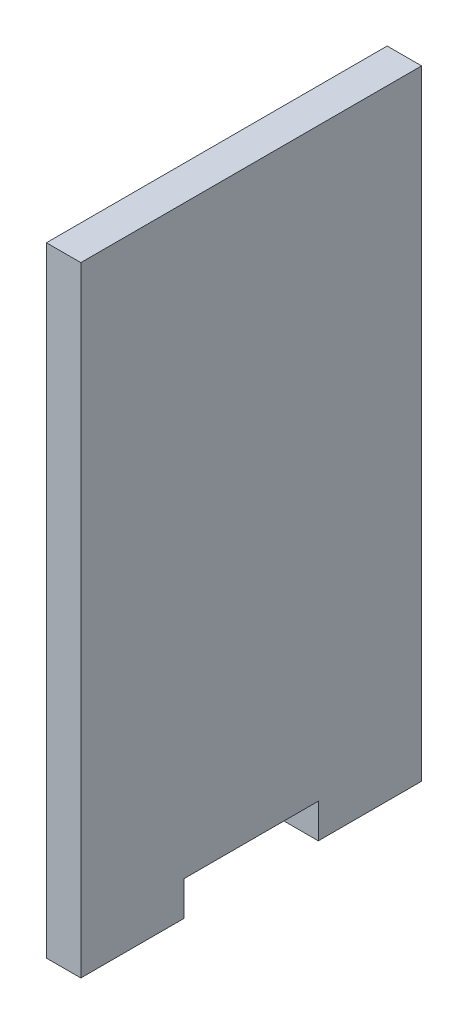
SolidWorks part; units mm, degrees
ref_plane "정면" through (0, 0, 0) normal (0, 0, 1) x (1, 0, 0)
ref_plane "윗면" through (0, 0, 0) normal (0, 1, 0) x (1, 0, 0)
ref_plane "우측면" through (0, 0, 0) normal (1, 0, 0) x (0, 0, -1)
sketch "스케치1" plane through (0, 0, 0) normal (1, 0, 0) x (0, 0, -1)
  line L1 (0, 43.267) -> (49.5, 43.267)
  line L2 (0, 43.267) -> (0, -41.733)
  line L3 (0, -41.733) -> (49.5, -41.733)
  line L4 (49.5, 43.267) -> (49.5, -41.733)
  dimension "D1" = 49.5
  dimension "D2" = 85
extrude "보스-돌출1" add sketch "스케치1" along normal blind 5
sketch "스케치2" plane through (5, 0, 0) normal (1, 0, 0) x (0, 0, -1)
  line L0 (0, -41.733) -> (49.5, -41.733) construction
  line L1 (0, -41.733) -> (91, -41.733)
  line L2 (0, -41.733) -> (0, -191.733)
  line L3 (0, -191.733) -> (91, -191.733)
  line L4 (91, -41.733) -> (91, -191.733)
  line L6 (0, 43.267) -> (0, -41.733) construction
  line L7 (91, -41.733) -> (90.889, 3.2199) construction
  dimension "D1" = 91
  dimension "D2" = 150
extrude "보스-돌출2" [suppressed] add sketch "스케치2" against normal blind 5
fillet "필렛1" [suppressed] radius 5
hole_wizard "M3 소켓 머리 캡 나사용 카운터보어1" [suppressed] positions "스케치4" profile "스케치3" counterbore size "M3" standard "KS"
sketch "스케치4" plane through (5, 0, 0) normal (1, 0, 0) x (0, 0, -1)
  line L0 (91, 23.267) -> (70.5, 23.267) construction
  line L2 (70.5, 23.267) -> (20.5, 23.267) construction
  line L3 (20.5, 23.267) -> (0, 23.267) construction
  line L5 (91, 43.267) -> (0, 43.267) construction
  point P2 (70.5, 23.267)
  point P6 (20.5, 23.267)
  dimension "D1" = 50
  dimension "D2" = 20
sketch "스케치3" plane through (5, 23.267, -70.5) normal (0, 1, 0) x (0, 0, -1)
  line L0 (0, 0) -> (0, 5)
  line L1 (0, 5) -> (1.7, 5)
  line L3 (1.7, 5) -> (1.7, 3)
  line L4 (1.7, 3) -> (3.25, 3)
  line L5 (3.25, 3) -> (3.25, 0)
  line L7 (3.25, 0) -> (0, 0)
  line L11 (0, -6.35) -> (0, 107.95) construction
  dimension "관통 구멍 지름" = 3.4
  dimension "관통 구멍 깊이" = 5
  dimension "카운터보어 지름" = 6.5
  dimension "카운터보어 깊이" = 3
hole_wizard "M3 소켓 머리 캡 나사용 카운터보어2" [suppressed] positions "스케치9" profile "스케치8" counterbore size "M3" standard "KS"
sketch "스케치9" plane through (0, 0, 0) normal (-1, 0, 0) x (0, 0, 1)
  line L0 (0, -39.233) -> (-12.25, -39.233) construction
  line L1 (0, 43.267) -> (0, -41.733) construction
  line L2 (-12.25, -39.233) -> (-37.25, -39.233) construction
  line L3 (-37.25, -39.233) -> (-49.5, -39.233) construction
  line L4 (-49.5, -41.733) -> (-49.5, 43.267) construction
  line L5 (0, -41.733) -> (-49.5, -41.733) construction
  point P2 (-12.25, -39.233)
  point P6 (-37.25, -39.233)
  dimension "D1" = 25
  dimension "D2" = 2.5
sketch "스케치8" plane through (0, -39.233, -12.25) normal (0, 1, 0) x (0, 0, 1)
  line L0 (0, 0) -> (0, 5)
  line L1 (0, 5) -> (1.7, 5)
  line L3 (1.7, 5) -> (1.7, 3)
  line L4 (1.7, 3) -> (3.25, 3)
  line L5 (3.25, 3) -> (3.25, 0)
  line L7 (3.25, 0) -> (0, 0)
  line L11 (0, -6.35) -> (0, 107.95) construction
  dimension "관통 구멍 지름" = 3.4
  dimension "관통 구멍 깊이" = 5
  dimension "카운터보어 지름" = 6.5
  dimension "카운터보어 깊이" = 3
hole_wizard "M3x0.5 나사 구멍1" [suppressed] positions "스케치11" profile "스케치10" tap size "M3x0.5" standard "Ansi Metric"
sketch "스케치11" plane through (0, -41.733, 0) normal (0, -1, 0) x (-1, 0, 0)
  line L0 (-2.5, 0) -> (-2.5, 12.25) construction
  line L1 (-5, 0) -> (0, 0) construction
  line L2 (-2.5, 12.25) -> (-2.5, 37.25) construction
  line L3 (-2.5, 37.25) -> (-2.5, 49.5) construction
  line L4 (-5, 49.5) -> (0, 49.5) construction
  point P2 (-2.5, 12.25)
  point P5 (-2.5, 37.25)
  dimension "D1" = 25
sketch "스케치10" plane through (2.5, -41.733, -12.25) normal (1, 0, 0) x (0, 0, -1)
  line L0 (0, 0) -> (0, 9.2511)
  line L1 (0, 9.2511) -> (1.25, 8.5)
  line L2 (1.25, 8.5) -> (1.25, 0)
  line L5 (1.25, 0) -> (0, 0)
  line L10 (0, 9.2511) -> (-1.25, 8.5) construction
  line L11 (0, -6.35) -> (0, 107.95) construction
  dimension "탭 드릴 지름" = 2.5
  dimension "탭 드릴 깊이" = 8.5
  dimension "드릴 각도" = 118
cosmetic thread "구멍 나사산1" [suppressed] parameters "D1"=6, "D2"=3
cosmetic thread "구멍 나사산2" [suppressed] parameters "D1"=6, "D2"=3
sketch "스케치12" plane through (5, 0, 0) normal (1, 0, 0) x (0, 0, -1)
  line L1 (49.5, -41.733) -> (34.5, -41.733)
  line L2 (49.5, -41.733) -> (49.5, -46.733)
  line L3 (49.5, -46.733) -> (34.5, -46.733)
  line L4 (34.5, -41.733) -> (34.5, -46.733)
  line L5 (0, -41.733) -> (15, -41.733)
  line L6 (0, -41.733) -> (0, -46.733)
  line L7 (0, -46.733) -> (15, -46.733)
  line L8 (15, -41.733) -> (15, -46.733)
  dimension "D1" = 15
  dimension "D2" = 15
  dimension "D3" = 5
  dimension "D4" = 5
extrude "보스-돌출3" add sketch "스케치12" against normal blind 5
